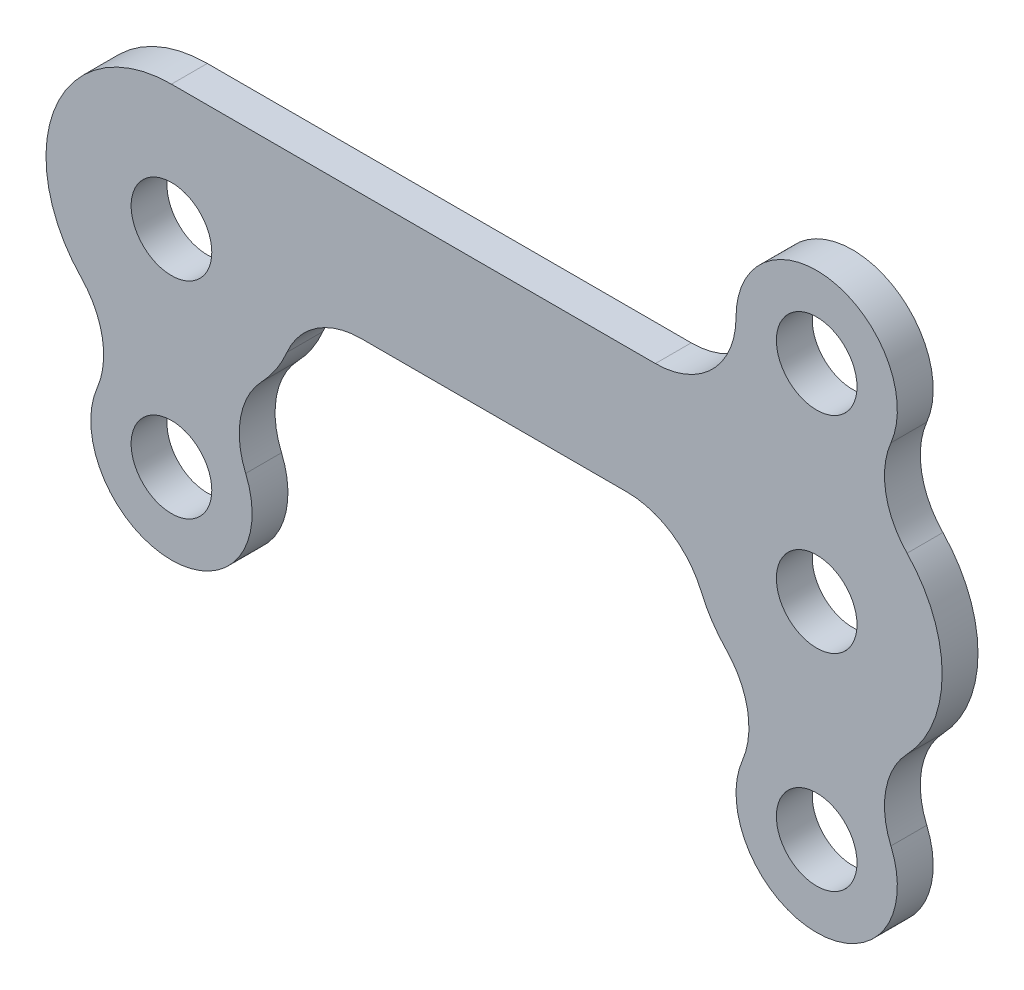
SolidWorks part; units mm, degrees
ref_plane "Front Plane" through (0, 0, 0) normal (0, 0, 1) x (1, 0, 0)
ref_plane "Top Plane" through (0, 0, 0) normal (0, 1, 0) x (1, 0, 0)
ref_plane "Right Plane" through (0, 0, 0) normal (1, 0, 0) x (0, 0, -1)
sketch "Sketch1" plane through (0, 0, 0) normal (0, 0, 1) x (1, 0, 0)
  line L0 (5.5562, 0) -> (23.0188, 0)
  line L1 (0, 5.5562) -> (28.575, 5.5562)
  line L5 (0, 5.5562) -> (28.575, 5.5562) construction
  circle A0 centre (0, 0) radius 5.5562 construction
  circle A1 centre (28.575, 0) radius 5.5562 construction
  arc A2 (0, 5.5562) -> (0, -5.5562) centre (0, 0) ccw
  arc A3 (28.575, -5.5562) -> (28.575, 5.5562) centre (28.575, 0) ccw
  circle A4 centre (0, 0) radius 1.7859
  circle A5 centre (28.575, 0) radius 1.7859
  arc A6 (0, -5.5562) -> (5.5562, 0) centre (0, 0) ccw
  arc A7 (23.0188, 0) -> (28.575, -5.5562) centre (28.575, 0) ccw
  circle A10 centre (0, -9.1281) radius 3.5719
  circle A12 centre (28.575, -9.1281) radius 1.7859
  circle A15 centre (0, -9.1281) radius 1.7859
  circle A17 centre (28.575, -9.1281) radius 3.5719
  circle A27 centre (-6.5741, -6.3327) radius 3.5719
  circle A28 centre (6.5741, -6.3327) radius 3.5719
  circle A29 centre (22.0009, -6.3327) radius 3.5719
  circle A30 centre (35.1491, -6.3327) radius 3.5719
  circle A31 centre (28.575, 9.1281) radius 1.7859
  circle A32 centre (28.575, 9.1281) radius 3.5719
  circle A33 centre (21.4313, 9.1281) radius 3.5719
  circle A34 centre (35.1491, 6.3327) radius 3.5719
  dimension "D1" = 28.575
  dimension "D2" = 11.1125
  dimension "D3" = 3.5719
  dimension "D6" = 7.1437
  dimension "D7" = 3.5719
extrude "Boss-Extrude1" add sketch "Sketch1" along normal blind 1.5875
fillet "Fillet1" radius 3.5719 2 edges at (23.0188, 0, 0.7937) (5.5562, 0, 0.7937)
